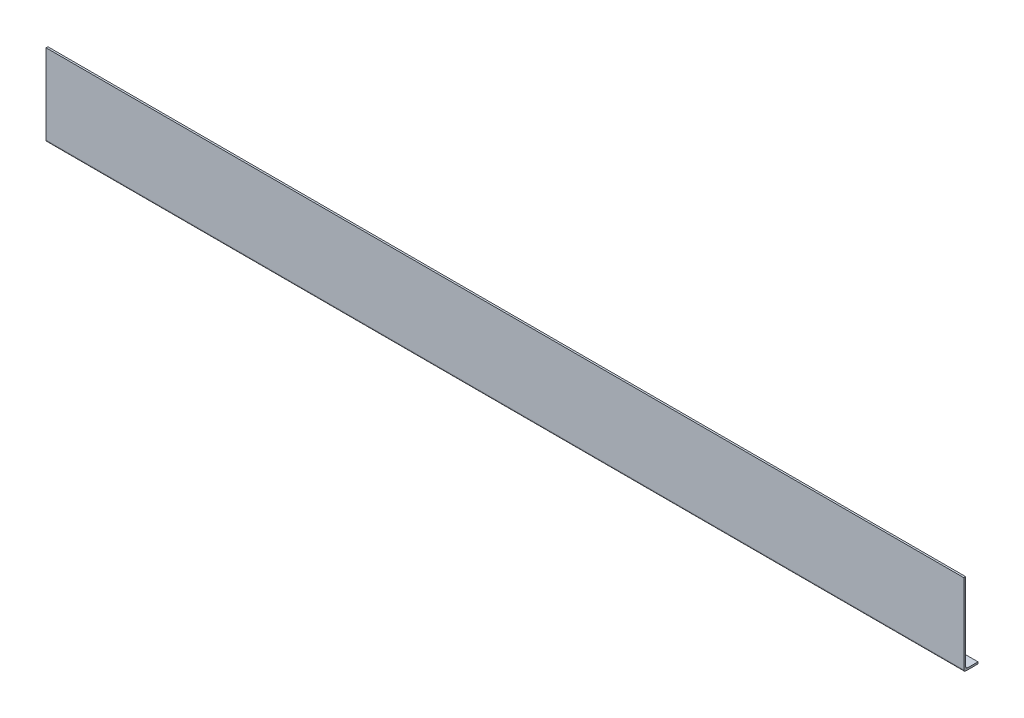
SolidWorks part; units mm, degrees
ref_plane "Front Plane" through (0, 0, 0) normal (0, 0, 1) x (1, 0, 0)
ref_plane "Top Plane" through (0, 0, 0) normal (0, 1, 0) x (1, 0, 0)
ref_plane "Right Plane" through (0, 0, 0) normal (1, 0, 0) x (0, 0, -1)
sketch "Sketch1" plane through (0, 0, 0) normal (1, 0, 0) x (0, 0, -1)
  line L0 (0, 0) -> (-23, 0)
  line L1 (-23, 0) -> (-23, 133)
  line L2 (0, 3) -> (-20, 3)
  line L3 (-20, 3) -> (-20, 133)
  line L4 (-23, 133) -> (-20, 133)
  line L5 (0, 3) -> (0, 0)
  dimension "D1" = 3
  dimension "D2" = 133
  dimension "D3" = 23
extrude "Boss-Extrude1" add sketch "Sketch1" along normal blind 1493
fillet "Fillet1" radius 3 2 edges at (746.5, 3, 20) (746.5, 0, 23)
equation "\"1Bar_Side_RF_3mm_length\"=1493.0"
equation "\"D1@Boss-Extrude1\"=\"1Bar_Side_RF_3mm_length\""
equation "\"CarBeamWidth\"=700.0"
equation "\"WheelWidth\"=650.0"
equation "\"Wheel_FrontBoxDistance\"=1390.0"
equation "\"MetalSheet_3mm_length\"=5030.0"
equation "\"MetalSheet_3mm_width\"=1923.0"
equation "\"MetalSheet_3mm_FloorCut_L_length\"=1764.0"
equation "\"MetalSheet_3mm_FloorCut_L_disdance\"=1665.0"
equation "\"MetalSheet_3mm_FloorCut_R_length\"=1764.0"
equation "\"MetalSheet_3mm_FloorCut_R_disdance\"=1665.0"
equation "\"indoorHeight\"=1940.0"
equation "\"haveDoor_R\"=1"
equation "\"DoorSeparator_RF_3mm_withHinge_toFrontDistance\"=1673.0"
equation "\"DoorSeparator_RF_3mm_withHinge_exist\"=1"
equation "\"DoorSeparator_RB_3mm_withHinge_toFrontDistance\"=3427.0"
equation "\"DoorSeparator_RB_3mm_withHinge_exist\"=1"
equation "\"Door_R1_L_open_Single_toFrontDistance\"=2547.5"
equation "\"Door_R1_L_open_Single_exist\"=1"
equation "\"Door_R1_R_open_Single_toFrontDistance\"=3422.0"
equation "\"Door_R1_R_open_Single_exist\"=1"
equation "\"x\"=66.0"
equation "\"da\"=62.0"
equation "\"SquareTube_length\"=1923.0"
equation "\"channelSteel_length\"=5030.0"
equation "\"SquareTube_inFront_AvgDistance\"=285.0"
equation "\"SquareTube_inFront_TotalCount\"=5"
equation "\"SquareTube_inFront1_cutDepth50_R\"=0.5"
equation "\"SquareTube_inFront1_cutDepth50_L\"=0.5"
equation "\"SquareTube_inFront2_cutDepth50_R\"=0.5"
equation "\"SquareTube_inFront2_cutDepth50_L\"=0.5"
equation "\"SquareTube_inFront3_cutDepth50_R\"=0.5"
equation "\"SquareTube_inFront3_cutDepth50_L\"=0.5"
equation "\"SquareTube_inFront4_cutDepth50_R\"=0.5"
equation "\"SquareTube_inFront4_cutDepth50_L\"=0.5"
equation "\"SquareTube_inFront5_cutDepth50_R\"=50"
equation "\"SquareTube_inFront5_cutDepth50_L\"=50"
equation "\"SquareTube_inFront6_cutDepth50_R\"=50"
equation "\"SquareTube_inFront6_cutDepth50_L\"=50"
equation "\"SquareTube_inFront7_cutDepth50_R\"=50"
equation "\"SquareTube_inFront7_cutDepth50_L\"=50"
equation "\"SquareTube_inFront8_cutDepth50_R\"=50"
equation "\"SquareTube_inFront8_cutDepth50_L\"=50"
equation "\"SquareTube_inFront9_cutDepth50_R\"=50"
equation "\"SquareTube_inFront9_cutDepth50_L\"=50"
equation "\"SquareTube_inFront10_cutDepth50_R\"=50"
equation "\"SquareTube_inFront10_cutDepth50_L\"=50"
equation "\"SquareTube_inFront11_cutDepth50_R\"=50"
equation "\"SquareTube_inFront11_cutDepth50_L\"=50"
equation "\"SquareTube_inFront12_cutDepth50_R\"=50"
equation "\"SquareTube_inFront12_cutDepth50_L\"=50"
equation "\"SquareTube_inFront13_cutDepth50_R\"=50"
equation "\"SquareTube_inFront13_cutDepth50_L\"=50"
equation "\"SquareTube_inFront14_cutDepth50_R\"=50"
equation "\"SquareTube_inFront14_cutDepth50_L\"=50"
equation "\"SquareTube_inBack_AvgDistance\"=333.125"
equation "\"SquareTube_inBack_TotalCount\"=9"
equation "\"SquareTube_inBack1_cutDepth50_R\"=50"
equation "\"SquareTube_inBack1_cutDepth50_L\"=50"
equation "\"SquareTube_inBack2_cutDepth50_R\"=50"
equation "\"SquareTube_inBack2_cutDepth50_L\"=50"
equation "\"SquareTube_inBack3_cutDepth50_R\"=50"
equation "\"SquareTube_inBack3_cutDepth50_L\"=50"
equation "\"SquareTube_inBack4_cutDepth50_R\"=50"
equation "\"SquareTube_inBack4_cutDepth50_L\"=50"
equation "\"SquareTube_inBack5_cutDepth50_R\"=50"
equation "\"SquareTube_inBack5_cutDepth50_L\"=50"
equation "\"SquareTube_inBack6_cutDepth50_R\"=0.5"
equation "\"SquareTube_inBack6_cutDepth50_L\"=0.5"
equation "\"SquareTube_inBack7_cutDepth50_R\"=0.5"
equation "\"SquareTube_inBack7_cutDepth50_L\"=0.5"
equation "\"SquareTube_inBack8_cutDepth50_R\"=0.5"
equation "\"SquareTube_inBack8_cutDepth50_L\"=0.5"
